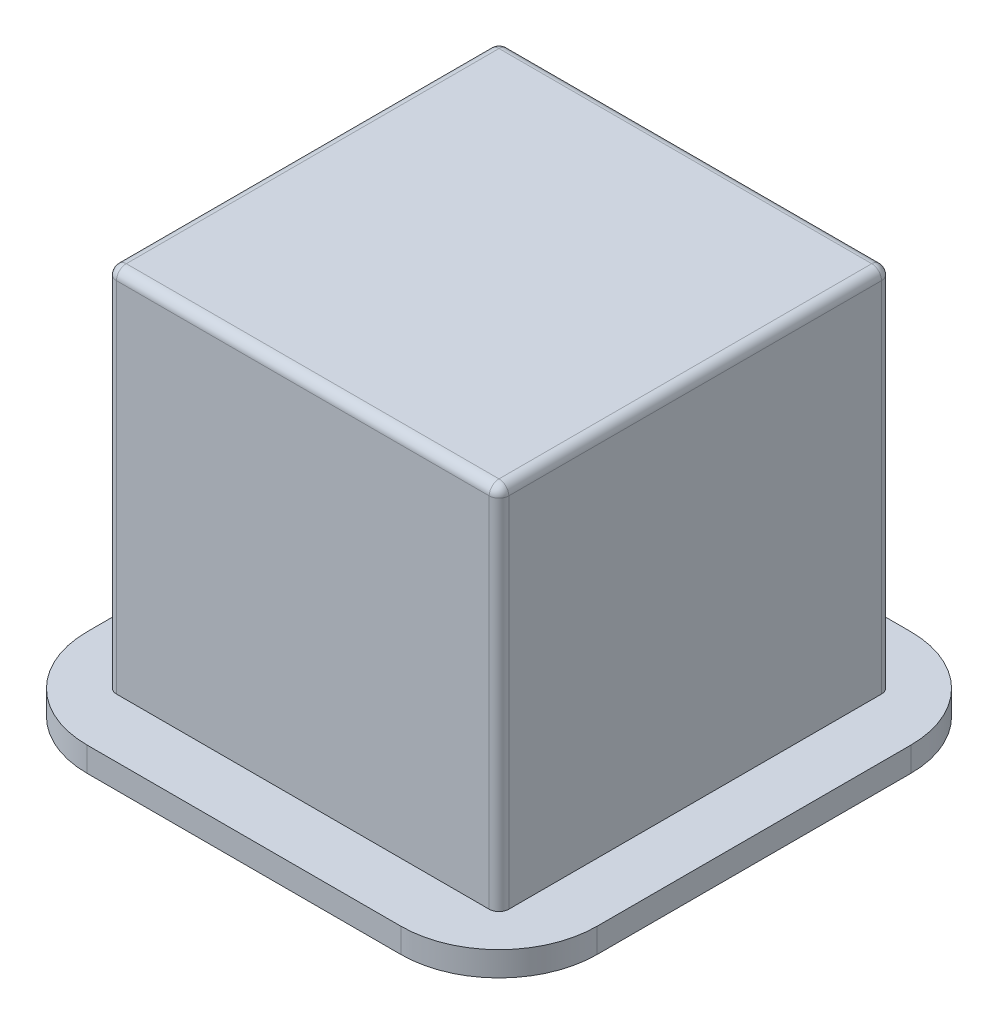
SolidWorks part; units mm, degrees
ref_plane "Front Plane" through (0, 0, 0) normal (0, 0, 1) x (1, 0, 0)
ref_plane "Top Plane" through (0, 0, 0) normal (0, 1, 0) x (1, 0, 0)
ref_plane "Right Plane" through (0, 0, 0) normal (1, 0, 0) x (0, 0, -1)
sketch "Sketch1" plane through (0, 0, 0) normal (0, 1, 0) x (1, 0, 0)
  line L1 (0, 0) -> (200, 0)
  line L2 (0, 0) -> (0, 200)
  line L3 (0, 200) -> (200, 200)
  line L4 (200, 0) -> (200, 200)
  dimension "D1" = 200
  dimension "D2" = 200
extrude "Boss-Extrude1" add sketch "Sketch1" along normal blind 200
sketch "Sketch3" plane through (0, 0, 0) normal (0, 0, 1) x (1, 0, 0)
  line L0 (200, 200) -> (200, 0) construction
  line L1 (0, 0) -> (200, 0)
  line L2 (0, 0) -> (0, 12.5)
  line L3 (0, 12.5) -> (200, 12.5)
  line L4 (200, 0) -> (200, 12.5)
  dimension "D1" = 12.5
extrude "Boss-Extrude2" add sketch "Sketch3" along normal blind 30
sketch "Sketch4" plane through (200, 0, 0) normal (1, 0, 0) x (0, 0, -1)
  line L1 (-30, 12.5) -> (200, 12.5)
  line L2 (-30, 12.5) -> (-30, 0)
  line L3 (-30, 0) -> (200, 0)
  line L4 (200, 12.5) -> (200, 0)
extrude "Boss-Extrude3" add sketch "Sketch4" along normal blind 30
sketch "Sketch5" plane through (0, 0, -200) normal (0, 0, -1) x (-1, 0, 0)
  line L1 (-230, 12.5) -> (0, 12.5)
  line L2 (-230, 12.5) -> (-230, 0)
  line L3 (-230, 0) -> (0, 0)
  line L4 (0, 12.5) -> (0, 0)
extrude "Boss-Extrude4" add sketch "Sketch5" along normal blind 30
sketch "Sketch6" plane through (0, 0, 0) normal (-1, 0, 0) x (0, 0, 1)
  line L1 (-230, 12.5) -> (30, 12.5)
  line L2 (-230, 12.5) -> (-230, 0)
  line L3 (-230, 0) -> (30, 0)
  line L4 (30, 12.5) -> (30, 0)
extrude "Boss-Extrude5" add sketch "Sketch6" along normal blind 30
fillet "Fillet1" radius 50 4 edges at (-30, 6.25, 30) (230, 6.25, 30) (230, 6.25, -230) (-30, 6.25, -230)
fillet "Fillet2" radius 5 8 edges at (200, 106.25, -200) (200, 106.25, 0) (100, 200, -200) (200, 200, -100) (0, 106.25, -200) (0, 200, -100) (100, 200, 0) (0, 106.25, 0)
